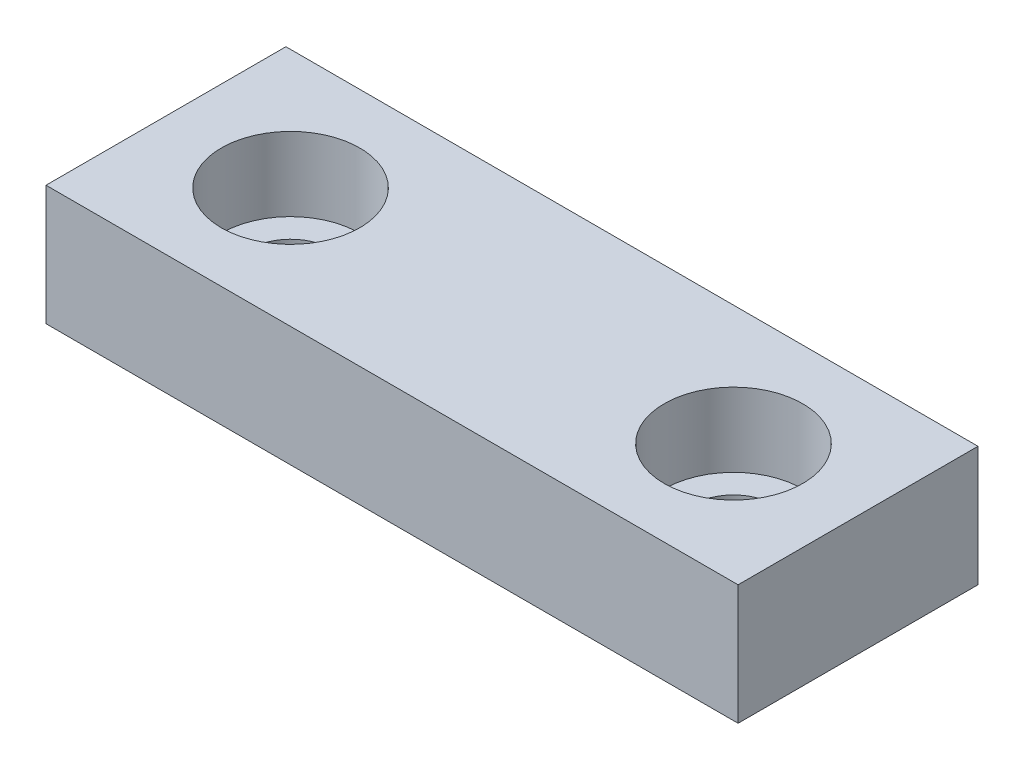
SolidWorks part; units mm, degrees
ref_plane "Front Plane" through (0, 0, 0) normal (0, 0, 1) x (1, 0, 0)
ref_plane "Top Plane" through (0, 0, 0) normal (0, 1, 0) x (1, 0, 0)
ref_plane "Right Plane" through (0, 0, 0) normal (1, 0, 0) x (0, 0, -1)
sketch "Sketch1" plane through (0, 0, 0) normal (0, 1, 0) x (1, 0, 0)
  line L0 (-37.5, -13) -> (37.5, -13)
  line L1 (0, 0) -> (37.5, 0) construction
  line L2 (0, 0) -> (0, 13) construction
  line L3 (-37.5, 13) -> (37.5, 13)
  line L4 (37.5, -13) -> (37.5, 13)
  line L5 (-37.5, -13) -> (-37.5, 13)
  point P8 (0, -13)
  dimension "D1" = 75
  dimension "D2" = 26
extrude "Extrude1" add sketch "Sketch1" along normal blind 13
hole_wizard "CBORE for M8 SHCS1" positions "Sketch4" profile "Sketch3" counterbore size "M8" standard "Ansi Metric" end condition through all
sketch "Sketch4" plane through (0, 13, 0) normal (0, 1, 0) x (-1, 0, 0)
  point P0 (24, 0)
  dimension "D1" = 24
sketch "Sketch3" plane through (-24, 13, 0) normal (1, 0, 0) x (0, 0, 1)
  line L0 (0, 0) -> (0, 13)
  line L1 (0, 13) -> (4.5, 13)
  line L3 (4.5, 13) -> (4.5, 8)
  line L4 (4.5, 8) -> (7.5, 8)
  line L5 (7.5, 8) -> (7.5, 0)
  line L7 (7.5, 0) -> (0, 0)
  line L11 (0, -6.35) -> (0, 107.95) construction
  dimension "Thru Hole Dia." = 9
  dimension "Thru Hole Depth" = 13
  dimension "C'Bore Dia." = 15
  dimension "C'Bore Depth" = 8
mirror "Mirror1" about plane through (0, 0, 0) normal (1, 0, 0) of "CBORE for M8 SHCS1"
